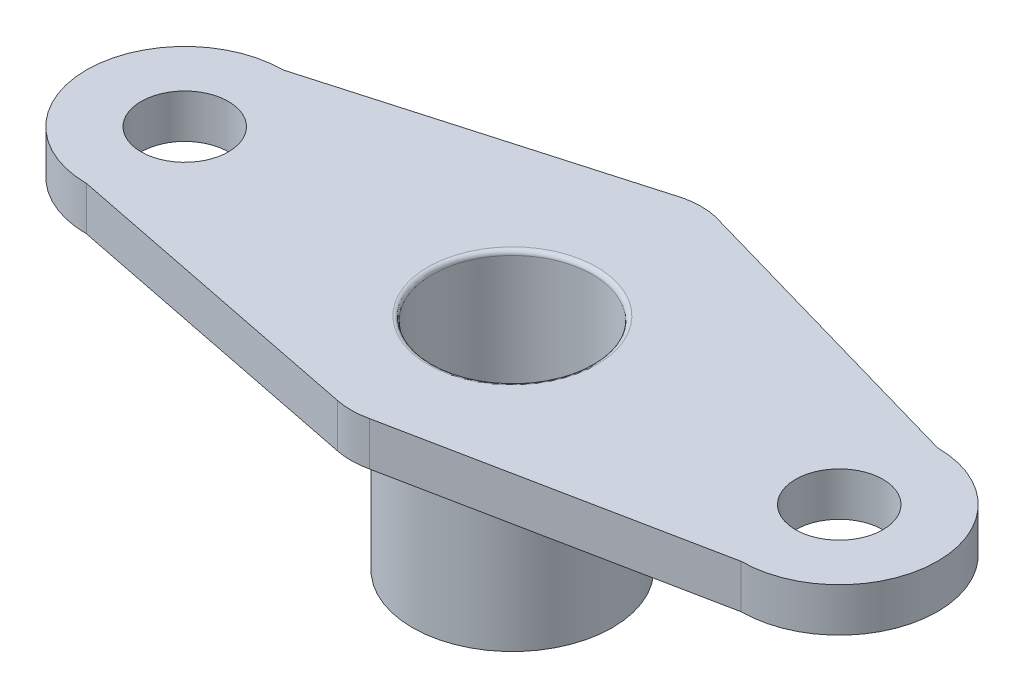
SolidWorks part; units mm, degrees
ref_plane "Front Plane" through (0, 0, 0) normal (0, 0, 1) x (1, 0, 0)
ref_plane "Top Plane" through (0, 0, 0) normal (0, 1, 0) x (1, 0, 0)
ref_plane "Right Plane" through (0, 0, 0) normal (1, 0, 0) x (0, 0, -1)
sketch "Sketch1" plane through (0, 0, 0) normal (0, 1, 0) x (1, 0, 0)
  line L0 (-75, -22.5) -> (-3.2, -36.8134)
  line L1 (-75, 22.5) -> (-3.7146, 42.9024)
  line L2 (-0.0884, 73.7505) -> (-0.0884, -110.1793) construction
  line L3 (4.0433, -36.7206) -> (74.8231, -22.5)
  line L4 (74.8231, 22.5) -> (3.5377, 42.9024)
  circle A0 centre (0, 0) radius 17.7855
  circle A1 centre (-75, 0) radius 10
  arc A2 (-75, 22.5) -> (-75, -22.5) centre (-75, 0) ccw
  arc A3 (-3.7146, 42.9024) -> (3.5377, 42.9024) centre (-0.0884, 26.1777) cw
  arc A4 (-3.2, -36.8134) -> (4.0433, -36.7206) centre (0.2074, -20.0428) ccw
  arc A5 (74.8231, 22.5) -> (74.8231, -22.5) centre (74.8231, 0) cw
  circle A6 centre (74.8231, 0) radius 10
  dimension "D1" = 75
  dimension "D2" = 20
  dimension "D3" = 22.5
  dimension "D4" = 80
  dimension "D5" = 80
extrude "Boss-Extrude1" add sketch "Sketch1" along normal mid plane 10
sketch "Sketch2" plane through (0, -5, 0) normal (0, -1, 0) x (1, 0, 0)
  circle A0 centre (0, 0) radius 22.8897
extrude "Boss-Extrude2" add sketch "Sketch2" along normal blind 40.3863 contours A0
sketch "Sketch4" plane through (0, -45.3863, 0) normal (0, -1, 0) x (1, 0, 0)
  circle A0 centre (0, 0) radius 18.3438
  point P3 (0, 0)
  point P4 (0, 0)
extrude "Cut-Extrude1" cut sketch "Sketch4" against normal blind 60
fillet "Fillet1" radius 1 1 edges at (0, 5, 18.3438)
